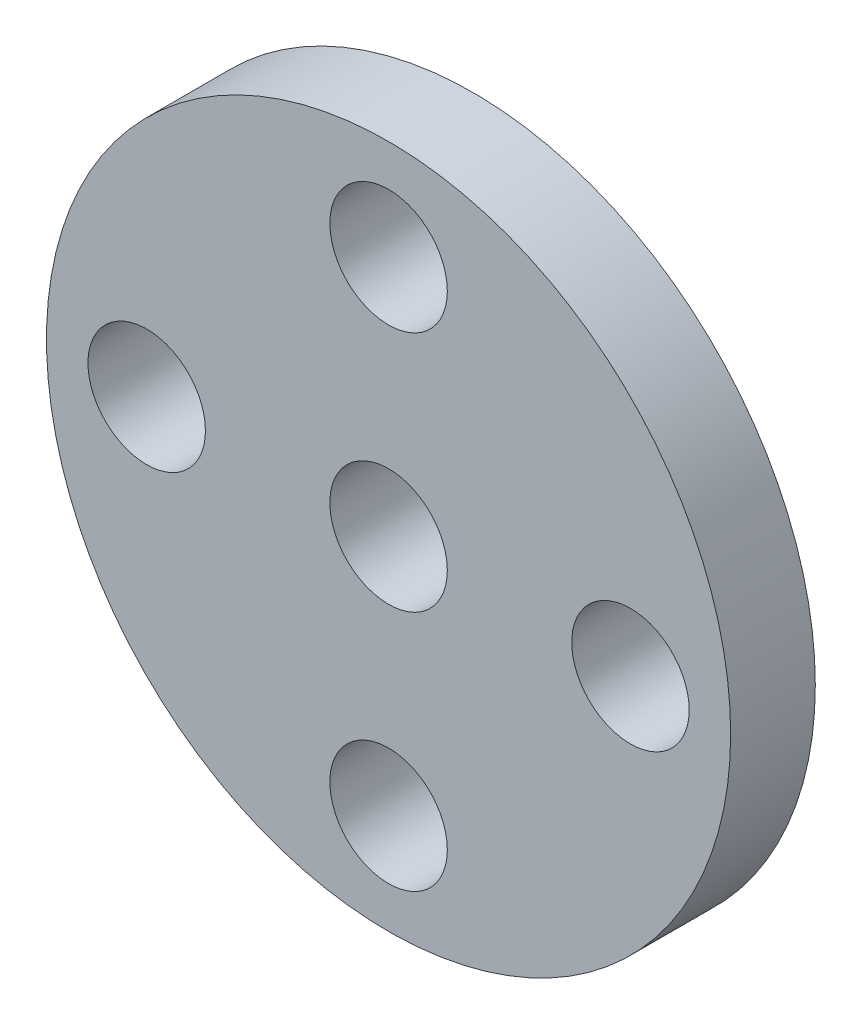
SolidWorks part; units mm, degrees
ref_plane "Front Plane" through (0, 0, 0) normal (0, 0, 1) x (1, 0, 0)
ref_plane "Top Plane" through (0, 0, 0) normal (0, 1, 0) x (1, 0, 0)
ref_plane "Right Plane" through (0, 0, 0) normal (1, 0, 0) x (0, 0, -1)
sketch "Sketch1" plane through (0, 0, 0) normal (0, 0, 1) x (1, 0, 0)
  line L0 (19.5, 0) -> (12.5, 0)
  circle A0 centre (19.5, 0) radius 9.9
  circle A1 centre (19.5, 0) radius 1.7
  circle A2 centre (19.5, 0) radius 4.5
  circle A3 centre (12.5, 0) radius 1.7
  circle A4 centre (19.5, 7) radius 1.7
  circle A5 centre (26.5, 0) radius 1.7
  circle A6 centre (19.5, -7) radius 1.7
  point P17 (19.5, 0)
  dimension "D1" = 4
extrude "Boss-Extrude2" add sketch "Sketch1" against normal blind 2.45
sketch "Sketch2" plane through (0, 0, -2.45) normal (0, 0, -1) x (-1, 0, 0)
  circle A0 centre (-19.5, 0) radius 2.0064
  circle A1 centre (-19.5, 0) radius 4.5
extrude "Boss-Extrude3" add sketch "Sketch2" along normal blind 2.05
